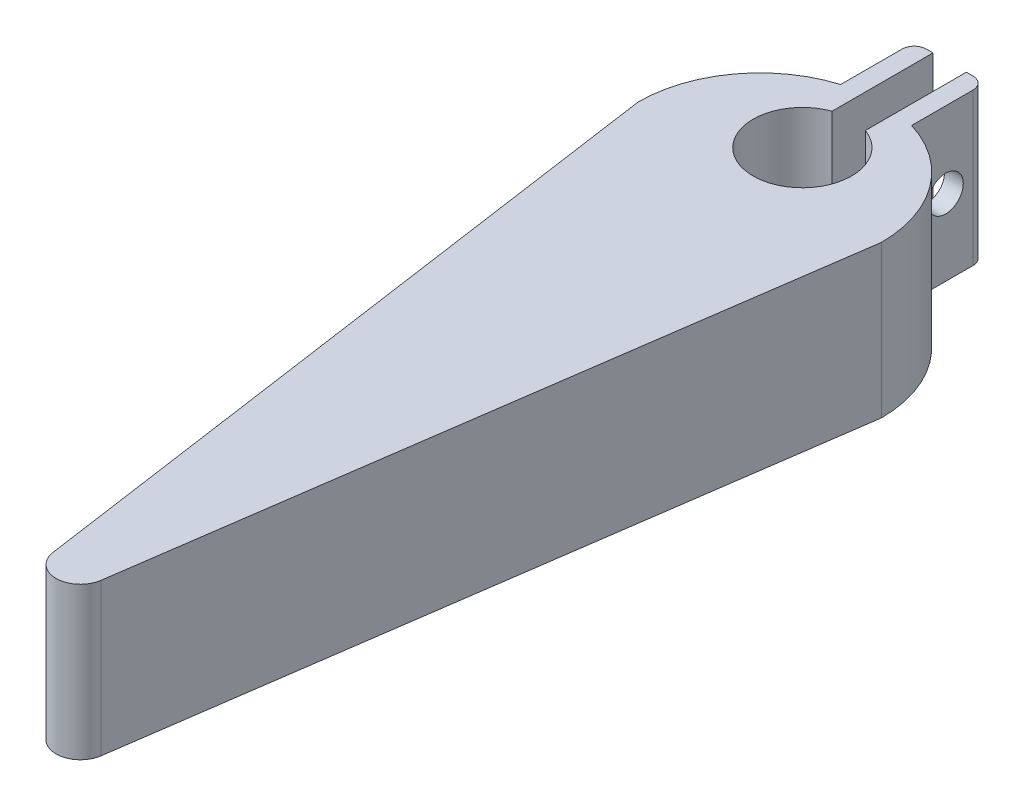
SolidWorks part; units mm, degrees
material "ABS"
ref_plane "Front Plane" through (0, 0, 0) normal (0, 0, 1) x (1, 0, 0)
ref_plane "Top Plane" through (0, 0, 0) normal (0, 1, 0) x (1, 0, 0)
ref_plane "Right Plane" through (0, 0, 0) normal (1, 0, 0) x (0, 0, -1)
sketch "Sketch2" plane through (0, 0, 0) normal (0, 1, 0) x (1, 0, 0)
  line L0 (0, 0) -> (0, -70) construction
  line L1 (-10, 0) -> (0, -70)
  line L2 (0, -70) -> (10, 0)
  arc A0 (-10, 0) -> (10, 0) centre (0, 0) cw
  circle A1 centre (0, 0) radius 4 construction
  circle A2 centre (0, 3.5) radius 4.05
  dimension "D1" = 10
  dimension "D3" = 8
  dimension "D4" = 8.1
  dimension "D2" = 70
  dimension "D5" = 3.5
extrude "Boss-Extrude1" add sketch "Sketch2" along normal blind 12.5
fillet "Fillet1" radius 2 1 edges at (0, 6.25, 70)
sketch "Sketch5" plane through (0, 12.5, 0) normal (0, 1, 0) x (1, 0, 0)
  line L0 (-1.3711, 3.7577) -> (-1.3711, 13.0509)
  line L1 (1.3741, 3.7566) -> (1.3741, 13.0509)
  line L2 (1.3741, 13.0509) -> (-1.3711, 13.0509)
  arc A0 (0, 4) -> (-1.3711, 3.7577) centre (0, 0) ccw
  arc A1 (0, 4) -> (1.3741, 3.7566) centre (0, 0) cw
extrude "Cut-Extrude1" cut sketch "Sketch5" against normal through all
sketch "Sketch6" plane through (0, 12.5, 0) normal (0, 1, 0) x (1, 0, 0)
  line L0 (-2.9179, 9.5648) -> (-2.9179, 15.6136)
  line L1 (-1.3711, 9.9056) -> (-1.3711, 15.6136)
  line L2 (-1.3711, 15.6136) -> (-2.9179, 15.6136)
  line L3 (1.3741, 9.9051) -> (1.3741, 15.6136)
  line L4 (1.3741, 15.6136) -> (2.9171, 15.6136)
  line L5 (2.9171, 15.6136) -> (2.9171, 9.5651)
  arc A0 (-1.3711, 9.9056) -> (-2.9179, 9.5648) centre (0, 0) ccw
  arc A1 (1.3741, 9.9051) -> (2.9171, 9.5651) centre (0, 0) cw
extrude "Boss-Extrude2" add sketch "Sketch6" against normal blind 12.5
fillet "Fillet2" radius 1 2 edges at (-2.9179, 6.25, -15.6136) (2.9171, 6.25, -15.6136)
sketch "Sketch7" plane through (2.9171, 0, 0) normal (1, 0, 0) x (0, 0, -1)
  line L0 (9.5651, 0) -> (9.5651, 12.5) construction
  line L1 (9.5651, 0) -> (14.6136, 0) construction
  circle A0 centre (12.3651, 6.25) radius 1.45
  dimension "D1" = 2.9
  dimension "D2" = 2.8
  dimension "D3" = 6.25
extrude "Cut-Extrude2" cut sketch "Sketch7" against normal through all
